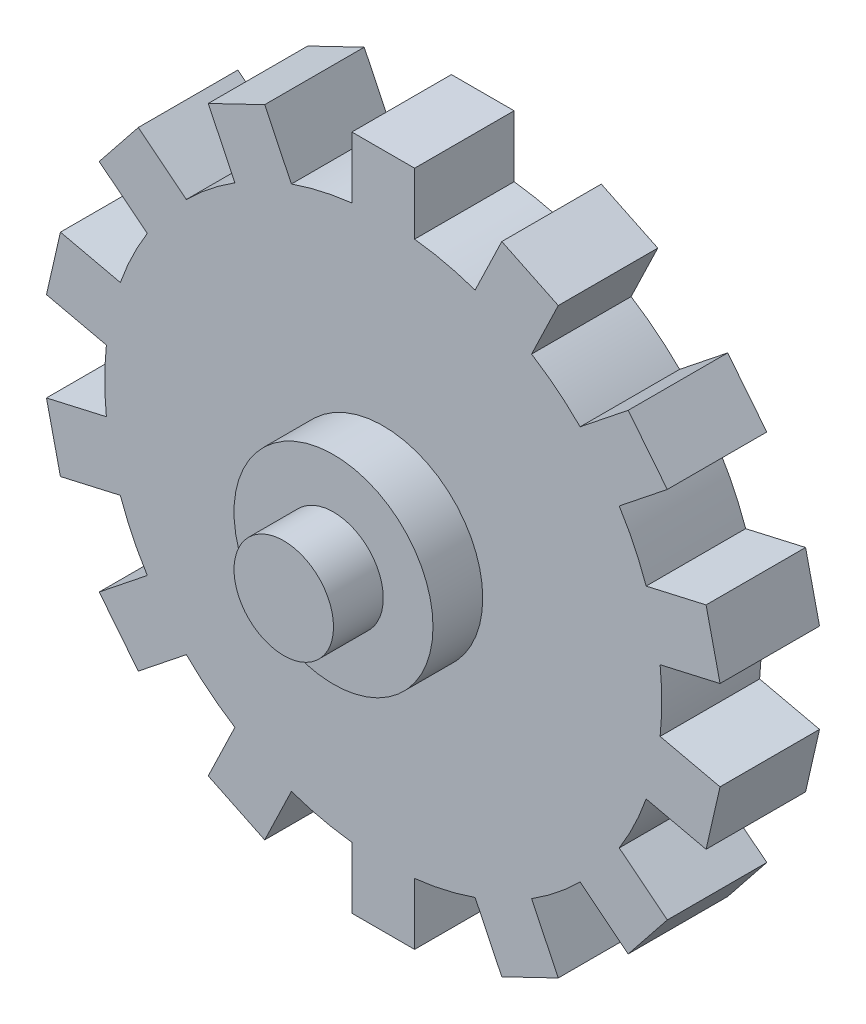
SolidWorks part; units mm, degrees
ref_plane "Front Plane" through (0, 0, 0) normal (0, 0, 1) x (1, 0, 0)
ref_plane "Top Plane" through (0, 0, 0) normal (0, 1, 0) x (1, 0, 0)
ref_plane "Right Plane" through (0, 0, 0) normal (1, 0, 0) x (0, 0, -1)
sketch "Sketch2" plane through (0, 0, 0) normal (0, 0, 1) x (1, 0, 0)
  circle A0 centre (0, 0) radius 28
  dimension "D1" = 56
extrude "Boss-Extrude1" add sketch "Sketch2" along normal mid plane 10
sketch "Sketch5" plane through (0, 0, 5) normal (0, 0, 1) x (1, 0, 0)
  line L1 (-3.15, 22) -> (3.15, 22)
  line L2 (-3.15, 22) -> (-3.15, 34)
  line L3 (-3.15, 34) -> (3.15, 34)
  line L4 (3.15, 22) -> (3.15, 34)
  line L5 (-3.15, 22) -> (3.15, 34) construction
  line L6 (-3.15, 34) -> (3.15, 22) construction
  circle A0 centre (0, 0) radius 28 construction
  point P0 (0, 28)
  dimension "D1" = 6.3
  dimension "D2" = 12
extrude "Boss-Extrude2" add sketch "Sketch5" against normal blind 10
pattern_circular "CirPattern1" count 14 over 360 about axis through (0, 0, 0) along (0, 0, 1) of "Boss-Extrude2"
sketch "Sketch6" plane through (0, 0, 5) normal (0, 0, 1) x (1, 0, 0)
  circle A0 centre (0, 0) radius 10
  dimension "D1" = 20
extrude "Boss-Extrude3" add sketch "Sketch6" along normal blind 5
sketch "Sketch7" plane through (0, 0, 10) normal (0, 0, 1) x (1, 0, 0)
  circle A0 centre (0, 0) radius 5
  dimension "D1" = 10
extrude "Boss-Extrude4" add sketch "Sketch7" along normal blind 5
mirror "Mirror1" about plane through (0, 0, 0) normal (0, 0, 1) of "Boss-Extrude3", "Boss-Extrude4"
